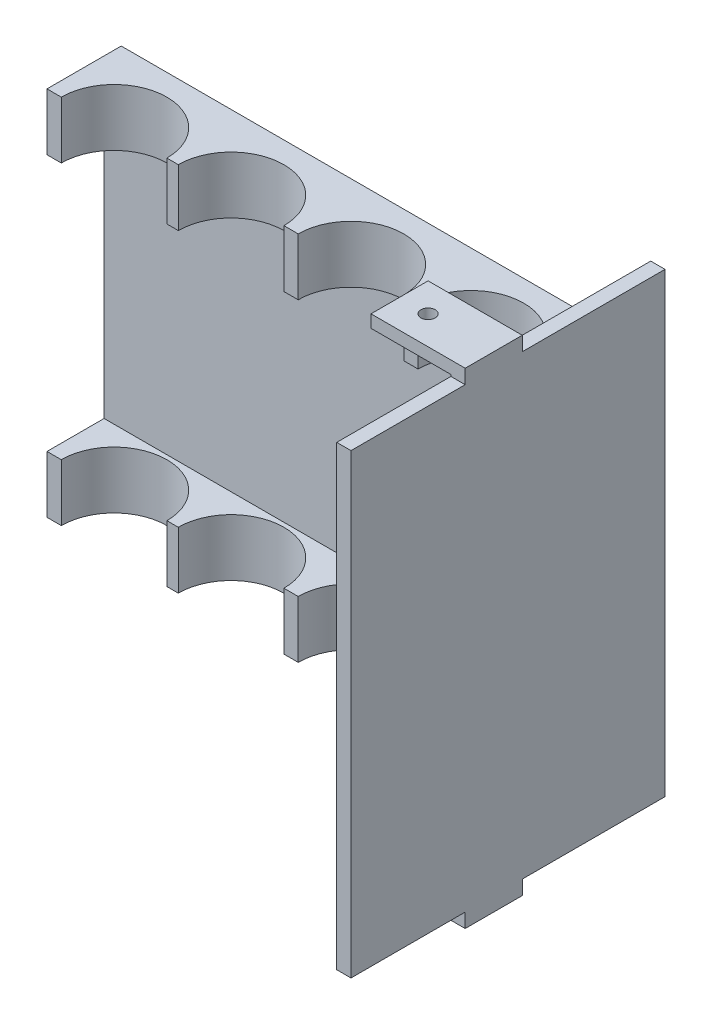
SolidWorks part; units mm, degrees
ref_plane "Plano frontal" through (0, 0, 0) normal (0, 0, 1) x (1, 0, 0)
ref_plane "Plano superior" through (0, 0, 0) normal (0, 1, 0) x (1, 0, 0)
ref_plane "Plano direito" through (0, 0, 0) normal (1, 0, 0) x (0, 0, -1)
sketch "Esboço1" plane through (0, 0, 0) normal (0, 0, 1) x (1, 0, 0)
  line L1 (0, 0) -> (80, 0)
  line L2 (0, 0) -> (0, 65)
  line L3 (0, 65) -> (80, 65)
  line L4 (80, 0) -> (80, 65)
extrude "Ressalto-extrusão1" add sketch "Esboço1" along normal blind 13
sketch "Esboço3" plane through (0, 0, 0) normal (-1, 0, 0) x (0, 0, 1)
  line L1 (0, 0) -> (13, 0)
  line L2 (0, 0) -> (0, 65)
  line L3 (0, 65) -> (13, 65)
  line L4 (13, 0) -> (13, 65)
extrude "Ressalto-extrusão2" add sketch "Esboço3" along normal blind 6.5
sketch "Esboço4" plane through (0, 0, 0) normal (0, -1, 0) x (-1, 0, 0)
  line L0 (6.5, -13) -> (-5.25, -13)
  line L1 (6.5, -13) -> (-80, -13) construction
  line L2 (-14.5, -13) -> (-25.75, -13)
  line L3 (-35, -13) -> (-46.75, -13)
  line L4 (-56, -13) -> (-67.75, -13)
  circle A0 centre (-5.25, -13) radius 9.25
  circle A1 centre (-25.75, -13) radius 9.25
  circle A2 centre (-46.75, -13) radius 9.25
  circle A3 centre (-67.75, -13) radius 9.25
  line M7 (-80, -13) -> (6.5, -13)
  dimension "D1" = 18.5
  dimension "D3" = 18.5
  dimension "D5" = 18.5
  dimension "D6" = 18.5
  dimension "D2" = 11.25
  dimension "D4" = 11.75
extrude "Corte-extrusão1" cut sketch "Esboço4" against normal blind 65 contours A0 M7 | A1 M7 | A2 M7 | A3 M7
sketch "Esboço5" plane through (80, 0, 0) normal (1, 0, 0) x (0, 0, -1)
  line L0 (-13, 0) -> (-13, 10)
  line L1 (-13, 0) -> (-13, 65) construction
  line L2 (-13, 10) -> (-3, 10)
  line L4 (-3, 10) -> (-3, 55)
  line L5 (-3, 55) -> (-13, 55)
  line L6 (-13, 55) -> (-13, 10)
  line M6 (-13, 65) -> (-13, 0)
  dimension "D1" = 10
  dimension "D2" = 10
  dimension "D3" = 45
extrude "Corte-extrusão2" cut sketch "Esboço5" against normal up to next contours L4 L5 L2 M6
sketch "Esboço6" plane through (80, 0, 0) normal (1, 0, 0) x (0, 0, -1)
  line L0 (0, 0) -> (0, 32.5)
  line L1 (0, 0) -> (0, 65) construction
  line L2 (0, 32.5) -> (6.25, 32.5)
  line L3 (6.25, 32.5) -> (6.25, -7.5)
  line L4 (6.25, -7.5) -> (-48.75, -7.5)
  line L5 (-48.75, -7.5) -> (-48.75, 72.5)
  line L6 (-48.75, 72.5) -> (6.25, 72.5)
  line L7 (6.25, 72.5) -> (6.25, 32.5)
  dimension "D1" = 6.25
  dimension "D2" = 40
  dimension "D3" = 55
  dimension "D4" = 80
extrude "Ressalto-extrusão4" add sketch "Esboço6" along normal blind 2.5
sketch "Esboço7" plane through (0, 72.5, 0) normal (0, 1, 0) x (1, 0, 0)
  line L1 (82.5, -48.75) -> (82.5, 6.25) construction
  line L7 (82.5, -28.75) -> (66, -28.75)
  line L8 (82.5, -28.75) -> (82.5, -18.75)
  line L9 (82.5, -18.75) -> (66, -18.75)
  line L10 (66, -28.75) -> (66, -18.75)
  dimension "D1" = 16.5
  dimension "D2" = 10
  dimension "D3" = 20
extrude "Ressalto-extrusão5" add sketch "Esboço7" along normal blind 2.5
ref_plane "Plano1" through (0, 32.5, 0) normal (0, -1, 0) x (-1, 0, 0)
mirror "Espelhar1" about plane through (0, 32.5, 0) normal (0, -1, 0) of "Ressalto-extrusão5"
sketch "Esboço9" plane through (0, 75, 0) normal (0, 1, 0) x (1, 0, 0)
  line L0 (66, -28.75) -> (82.5, -28.75) construction
  line L1 (66, -18.75) -> (66, -28.75) construction
  circle A0 centre (71, -23.75) radius 1.25
  dimension "D2" = 5
  dimension "D3" = 2.5
  dimension "D1" = 5
extrude "Corte-extrusão3" cut sketch "Esboço9" against normal through all
sketch "Esboço11" plane through (0, 72.5, 0) normal (0, -1, 0) x (1, 0, 0)
  line L0 (80, 18.75) -> (66, 18.75) construction
  line L1 (66, 18.75) -> (66, 28.75) construction
  line L2 (80, 18.75) -> (66, 18.75)
  line L3 (66, 18.75) -> (66, 28.75)
  line L4 (80, 28.75) -> (80, 18.75)
  line L5 (66, 28.75) -> (80, 28.75)
extrude "Corte-extrusão4" cut sketch "Esboço11" against normal blind 0.3
mirror "Espelhar2" about plane through (0, 32.5, 0) normal (0, -1, 0) of "Corte-extrusão4"
